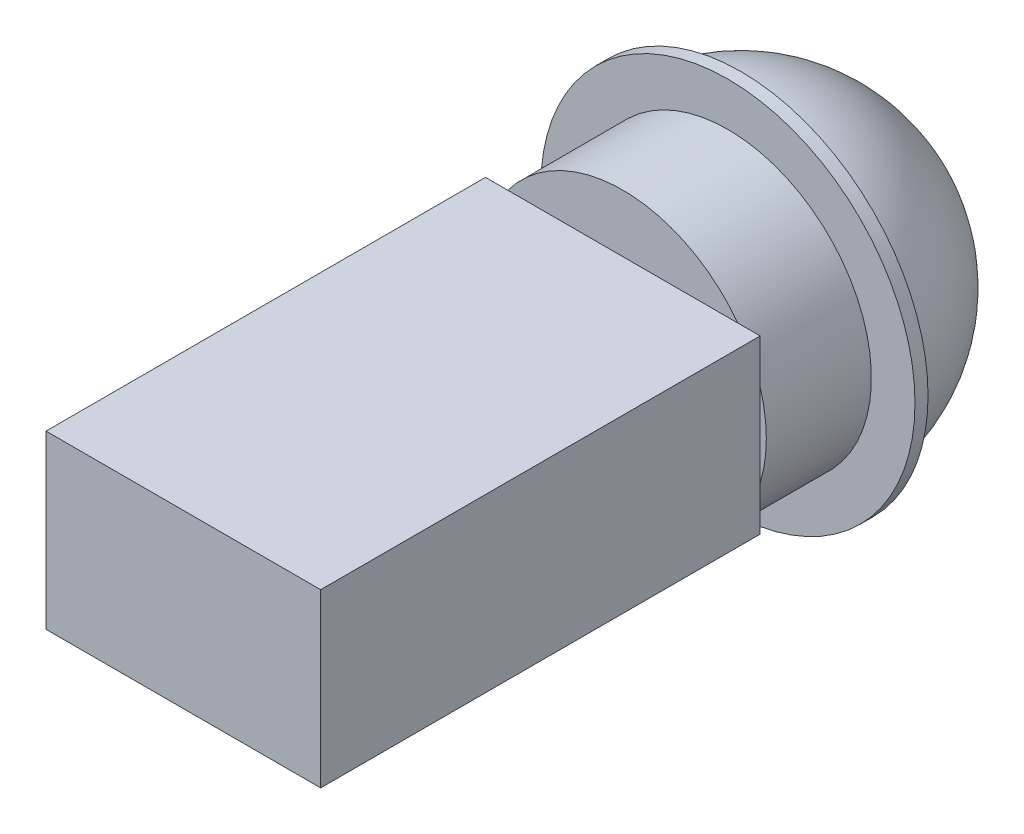
SolidWorks part; units mm, degrees
ref_plane "Front Plane" through (0, 0, 0) normal (0, 0, 1) x (1, 0, 0)
ref_plane "Top Plane" through (0, 0, 0) normal (0, 1, 0) x (1, 0, 0)
ref_plane "Right Plane" through (0, 0, 0) normal (1, 0, 0) x (0, 0, -1)
sketch "Sketch1" plane through (0, 0, 0) normal (0, 1, 0) x (1, 0, 0)
  line L0 (0, 6.2039) -> (0, -4.3688)
  line L1 (0, -4.3688) -> (-5.3086, -4.3688)
  line L2 (-5.3086, -4.3688) -> (-5.3086, -0.4826)
  line L3 (-5.3086, -0.4826) -> (-6.9215, -0.4826)
  line L4 (-6.9215, -0.4826) -> (-6.9215, 0)
  line L5 (-6.9215, 0) -> (-6.2039, 0)
  line L6 (0, 6.2039) -> (13.3606, 6.2039) construction
  arc A0 (-6.2039, 0) -> (0, 6.2039) centre (0, 0) cw
  point P9 (0, 0)
  point P11 (-5.867, 0)
  dimension "D1" = 0.4826
  dimension "D2" = 6.9215
  dimension "D3" = 6.2039
  dimension "D4" = 5.3086
  dimension "D5" = 3.8862
revolve "Revolve1" add sketch "Sketch1" angle 360 about L0
sketch "Sketch2" plane through (0, 0, 4.3688) normal (0, 0, 1) x (1, 0, 0)
  line L1 (5.08, 3.175) -> (-5.08, 3.175)
  line L2 (5.08, 3.175) -> (5.08, -3.175)
  line L3 (5.08, -3.175) -> (-5.08, -3.175)
  line L4 (-5.08, 3.175) -> (-5.08, -3.175)
  line L5 (5.08, 3.175) -> (-5.08, -3.175) construction
  line L6 (5.08, -3.175) -> (-5.08, 3.175) construction
  point P0 (0, 0)
  dimension "D1" = 10.16
  dimension "D2" = 6.35
extrude "Boss-Extrude1" add sketch "Sketch2" along normal blind 16.256
